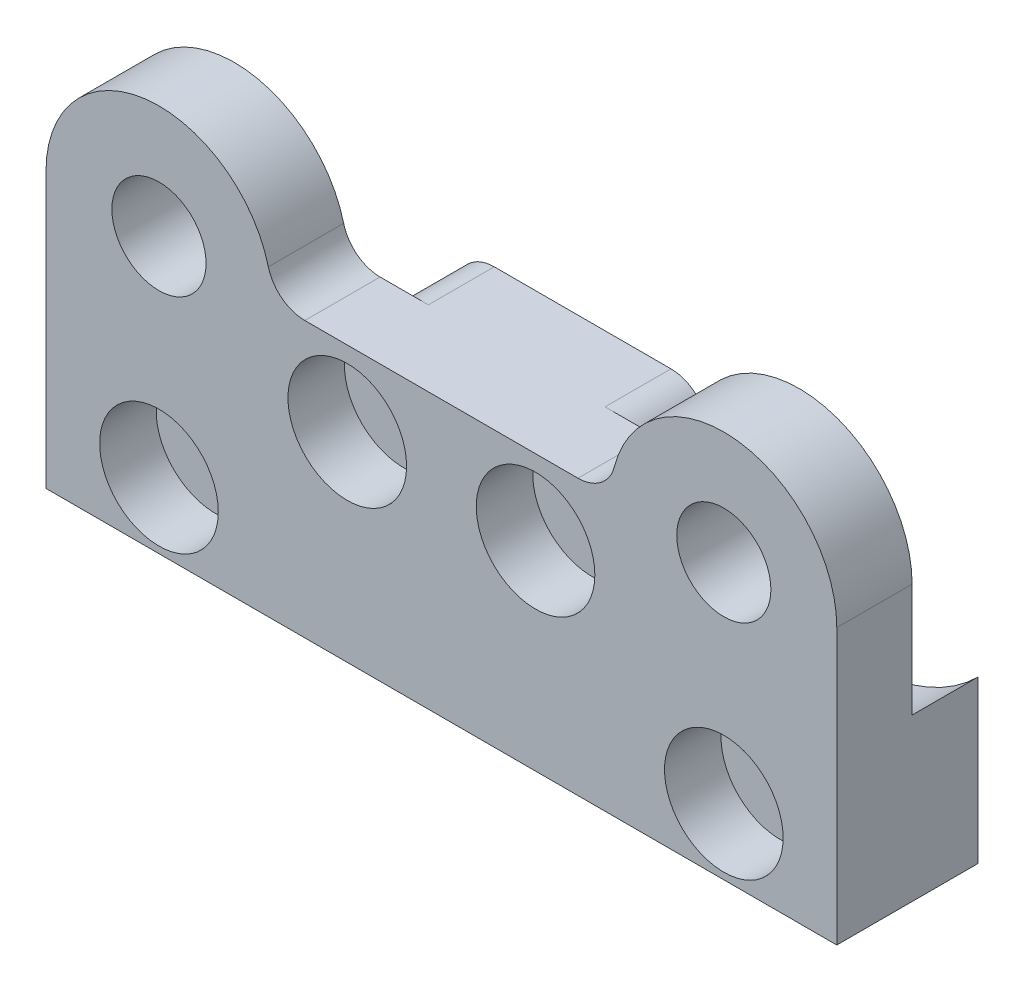
SolidWorks part; units mm, degrees
ref_plane "Front Plane" through (0, 0, 0) normal (0, 0, 1) x (1, 0, 0)
ref_plane "Top Plane" through (0, 0, 0) normal (0, 1, 0) x (1, 0, 0)
ref_plane "Right Plane" through (0, 0, 0) normal (1, 0, 0) x (0, 0, -1)
sketch "Sketch1" plane through (0, 0, 0) normal (0, 0, 1) x (1, 0, 0)
  line L0 (0, 0) -> (0, -69.5054) construction
  line L1 (-9, -41.3642) -> (9, -41.3642)
  line L2 (-21, -41.3642) -> (-21, -55.9642)
  line L3 (-21, -55.9642) -> (21, -55.9642)
  line L4 (21, -55.9642) -> (21, -41.3642)
  circle A0 centre (0, 0) radius 37 construction
  circle A1 centre (15, -41.3642) radius 7 construction
  circle A2 centre (15, -41.3642) radius 2.5
  circle A3 centre (15, -41.3642) radius 6
  circle A4 centre (-15, -41.3642) radius 2.5
  circle A5 centre (-15, -41.3642) radius 6
  dimension "D1" = 74
  dimension "D2" = 14
  dimension "D4" = 5
  dimension "D5" = 12
  dimension "D3" = 30
  dimension "D6" = 14.6
extrude "Boss-Extrude1" add sketch "Sketch1" along normal blind 4 contours L1 A5 L2 L3 L4 A3 | A5 A4 | A3 A2
sketch "Sketch2" plane through (0, 0, 0) normal (0, 0, -1) x (-1, 0, 0)
  circle A0 centre (15, -41.3642) radius 2.5 construction
  circle A1 centre (-15, -41.3642) radius 2.5 construction
  circle A2 centre (15, -41.3642) radius 2.5
  circle A3 centre (-15, -41.3642) radius 2.5
  circle A4 centre (-15, -41.3642) radius 4.25
  circle A5 centre (15, -41.3642) radius 4.25
  dimension "D1" = 8.5
extrude "Boss-Extrude2" add sketch "Sketch2" along normal blind 0.8
sketch "Sketch3" plane through (0, 0, 0) normal (0, 0, -1) x (-1, 0, 0)
  line L0 (9, -41.3642) -> (-9, -41.3642) construction
  line L1 (9, -41.3642) -> (-9, -41.3642)
  line L2 (21, -55.9642) -> (-21, -55.9642) construction
  line L3 (21, -41.3642) -> (21, -55.9642) construction
  line L4 (-21, -55.9642) -> (-21, -41.3642) construction
  line L5 (21, -55.9642) -> (-21, -55.9642)
  line L6 (21, -41.3642) -> (21, -55.9642)
  line L7 (-21, -55.9642) -> (-21, -41.3642)
  circle A0 centre (-15, -41.3642) radius 8.5
  circle A1 centre (15, -41.3642) radius 8.5
  line M5 (-21, -55.9642) -> (21, -55.9642)
  line M6 (21, -55.9642) -> (21, -41.3642)
  dimension "D1" = 17
extrude "Boss-Extrude3" add sketch "Sketch3" along normal blind 3.5 contours A1 L1 A0 L7 M5 M6
sketch "Sketch4" plane through (0, 0, -3.5) normal (0, 0, -1) x (-1, 0, 0)
  line L0 (-21, -52.4642) -> (21, -52.4642) construction
  line L3 (-5, -41.3642) -> (-5, -55.9642) construction
  line L4 (6.5, -41.3642) -> (-6.5, -41.3642) construction
  line L5 (-21, -55.9642) -> (21, -55.9642) construction
  line L6 (0, -55.9642) -> (0, -41.3642) construction
  line L7 (-5, -45.3642) -> (0, -45.3642) construction
  line L8 (-15, -49.8642) -> (-15, -52.4642) construction
  arc A0 (-21, -47.385) -> (-6.5, -41.3642) centre (-15, -41.3642) ccw construction
  circle A1 centre (-5, -45.3642) radius 1.6
  circle A2 centre (-15, -52.4642) radius 1.6
  circle A3 centre (15, -52.4642) radius 1.6
  circle A4 centre (5, -45.3642) radius 1.6
  point P2 (-21, -51.6746)
  dimension "D3" = 3.2
  dimension "D1" = 1.5
  dimension "D2" = 4
  dimension "D4" = 3.5
extrude "Cut-Extrude1" cut sketch "Sketch4" against normal through all
sketch "Sketch5" plane through (0, 0, 4) normal (0, 0, 1) x (1, 0, 0)
  circle A0 centre (-5, -45.3642) radius 3.15
  circle A1 centre (5, -45.3642) radius 3.15
  circle A2 centre (15, -52.4642) radius 3.15
  circle A3 centre (-15, -52.4642) radius 3.15
  dimension "D1" = 6.3
extrude "Cut-Extrude2" cut sketch "Sketch5" against normal blind 3
chamfer "Chamfer1" distance 0.5 angle 45 2 edges at (10.75, -41.3642, -0.8) (-19.25, -41.3642, -0.8)
fillet "Fillet1" radius 2 4 edges at (9, -41.3642, 2) (-9, -41.3642, 2) (-6.5, -41.3642, -1.75) (6.5, -41.3642, -1.75)
sketch "Sketch6" plane through (0, 0, 1) normal (0, 0, 1) x (1, 0, 0)
  circle A0 centre (15, -52.4642) radius 1.6 construction
  circle A1 centre (5, -45.3642) radius 1.6 construction
  circle A2 centre (-15, -52.4642) radius 1.6 construction
  circle A3 centre (-5, -45.3642) radius 1.6 construction
  circle A4 centre (15, -52.4642) radius 1.6
  circle A5 centre (5, -45.3642) radius 1.6
  circle A6 centre (-15, -52.4642) radius 1.6
  circle A7 centre (-5, -45.3642) radius 1.6
extrude "Boss-Extrude4" add sketch "Sketch6" against normal blind 0.4
